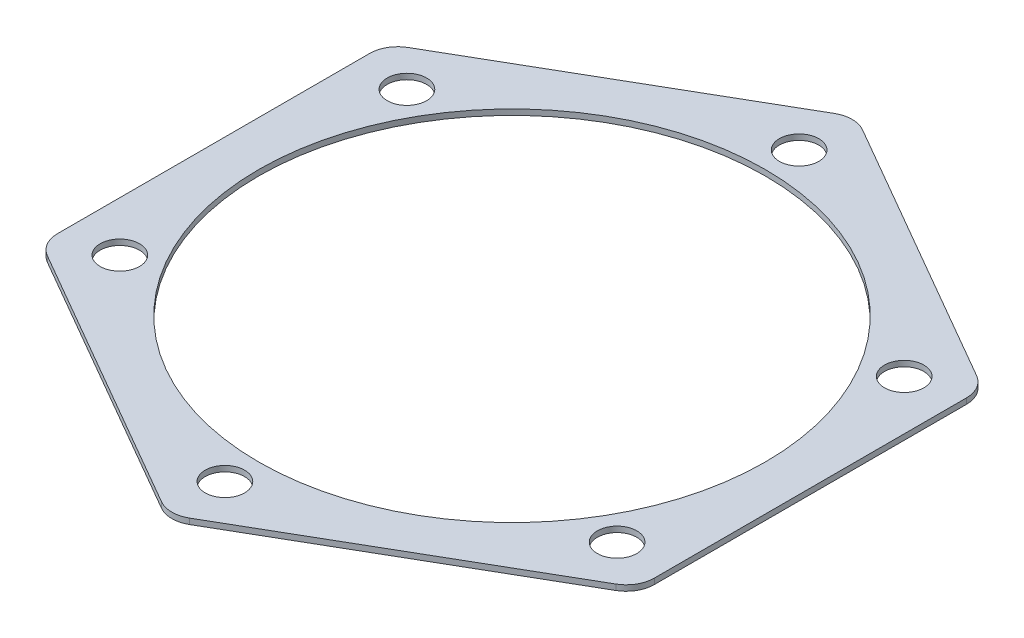
SolidWorks part; units mm, degrees
ref_plane "Front Plane" through (0, 0, 0) normal (0, 0, 1) x (1, 0, 0)
ref_plane "Top Plane" through (0, 0, 0) normal (0, 1, 0) x (1, 0, 0)
ref_plane "Right Plane" through (0, 0, 0) normal (1, 0, 0) x (0, 0, -1)
sketch "Sketch1" plane through (0, 0, 0) normal (0, 1, 0) x (1, 0, 0)
  line L1 (-2.5, 59.7558) -> (-50.5, 32.0429)
  line L2 (-53, 27.7128) -> (-53, -27.7128)
  line L3 (-50.5, -32.0429) -> (-2.5, -59.7558)
  line L4 (2.5, -59.7558) -> (50.5, -32.0429)
  line L5 (53, -27.7128) -> (53, 27.7128)
  line L6 (50.5, 32.0429) -> (2.5, 59.7558)
  circle A0 centre (0, 0) radius 53 construction
  arc A1 (50.5, -32.0429) -> (53, -27.7128) centre (48, -27.7128) ccw
  arc A2 (-2.5, -59.7558) -> (2.5, -59.7558) centre (0, -55.4256) ccw
  arc A3 (-53, -27.7128) -> (-50.5, -32.0429) centre (-48, -27.7128) ccw
  arc A4 (-50.5, 32.0429) -> (-53, 27.7128) centre (-48, 27.7128) ccw
  arc A5 (53, 27.7128) -> (50.5, 32.0429) centre (48, 27.7128) ccw
  arc A6 (-2.5, 59.7558) -> (2.5, 59.7558) centre (0, 55.4256) cw
  circle A7 centre (0, 0) radius 45
  circle A8 centre (0, 0) radius 51 construction
  circle A9 centre (0, 51) radius 3.5
  circle A10 centre (44.1673, 25.5) radius 3.5
  circle A11 centre (44.1673, -25.5) radius 3.5
  circle A12 centre (0, -51) radius 3.5
  circle A13 centre (-44.1673, -25.5) radius 3.5
  circle A14 centre (-44.1673, 25.5) radius 3.5
  point P38 (0, 0)
  dimension "D2" = 5
  dimension "D3" = 90
  dimension "D4" = 102
  dimension "D5" = 7
  dimension "D1" = 106
  dimension "D6" = 6
extrude "Boss-Extrude1" add sketch "Sketch1" along normal blind 1
